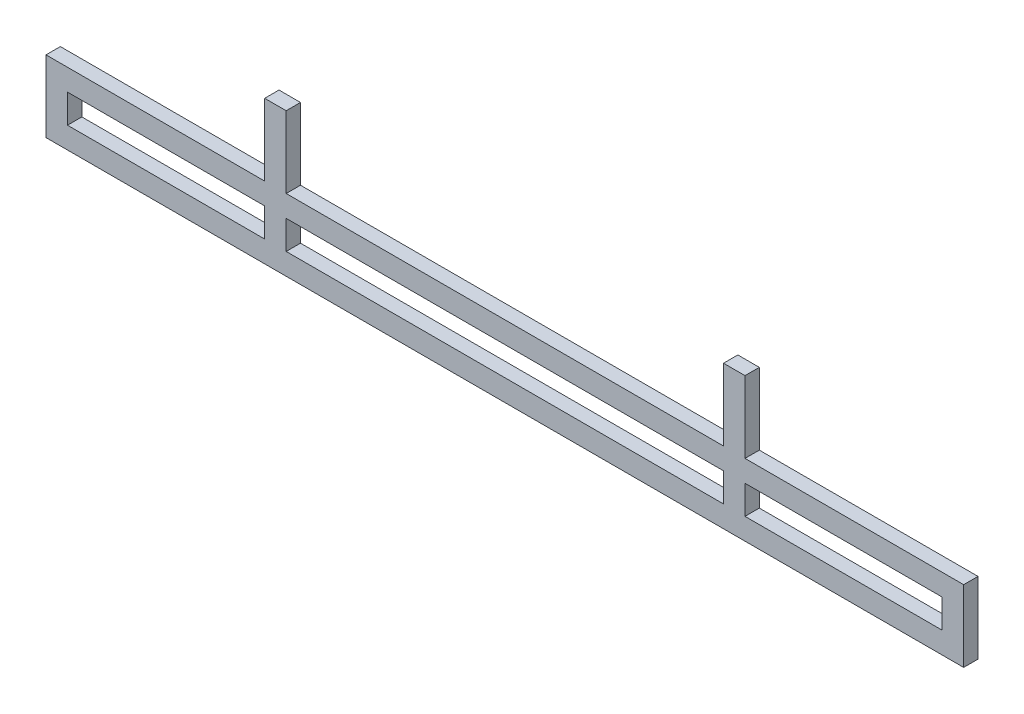
SolidWorks part; units mm, degrees
ref_plane "Front Plane" through (0, 0, 0) normal (0, 0, 1) x (1, 0, 0)
ref_plane "Top Plane" through (0, 0, 0) normal (0, 1, 0) x (1, 0, 0)
ref_plane "Right Plane" through (0, 0, 0) normal (1, 0, 0) x (0, 0, -1)
sketch "Sketch1" plane through (0, 0, 0) normal (0, 0, 1) x (1, 0, 0)
  line L1 (0, -145.36) -> (-640, -145.36)
  line L2 (0, -145.36) -> (0, -95.36)
  line L3 (0, -95.36) -> (-640, -95.36)
  line L4 (-640, -145.36) -> (-640, -95.36)
  dimension "D2" = 50
extrude "Boss-Extrude1" add sketch "Sketch1" along normal blind 10
sketch "Sketch2" plane through (0, 0, 0) normal (0, 0, 1) x (1, 0, 0)
  line L6 (-480, -145.36) -> (-480, -95.36) construction
  line L22 (-640, -95.36) -> (-640, -145.36) construction
  line L31 (-320, -145.36) -> (-320, -120.36) construction
  line L36 (-640, -145.36) -> (0, -145.36) construction
  line L37 (-320, -120.36) -> (-640, -120.36) construction
  line L38 (0, -95.36) -> (-640, -95.36) construction
  line L39 (-487.5, -95.36) -> (-472.5, -95.36)
  line L40 (-487.5, -95.36) -> (-487.5, -45.36)
  line L41 (-487.5, -45.36) -> (-472.5, -45.36)
  line L42 (-472.5, -95.36) -> (-472.5, -45.36)
  line L43 (-630, -45.36) -> (-487.5, -45.36) construction
  line L44 (-487.5, -95.36) -> (-487.5, -45.36)
  line L45 (-472.5, -95.36) -> (-472.5, -45.36)
  line L46 (-160, -145.36) -> (-160, -95.36) construction
  line L47 (-167.5, -95.36) -> (-167.5, -45.36)
  line L48 (-152.5, -95.36) -> (-152.5, -45.36)
  line L49 (-167.5, -95.36) -> (-167.5, -45.36)
  line L50 (-152.5, -45.36) -> (-167.5, -45.36)
  line L51 (-152.5, -95.36) -> (-152.5, -45.36)
  line L52 (-152.5, -95.36) -> (-167.5, -95.36)
  point P5 (-480, -120.36)
  point P19 (-480, -120.36)
  point P20 (-480, -95.36)
  line M30 (-640, -95.36) -> (0, -95.36)
  dimension "D1" = 15
extrude "Boss-Extrude2" add sketch "Sketch2" along normal blind 10 contours L50 L48 L47 M30 | L40 L39 L42 L41
sketch "Sketch3" plane through (0, 0, 0) normal (0, 0, -1) x (-1, 0, 0)
  line L0 (0, -95.36) -> (152.5, -95.36) construction
  line L1 (625, -110.36) -> (15, -110.36)
  line L2 (625, -110.36) -> (625, -130.36)
  line L3 (625, -130.36) -> (15, -130.36)
  line L4 (15, -110.36) -> (15, -130.36)
  line L5 (640, -145.36) -> (0, -145.36) construction
  line L6 (0, -145.36) -> (0, -95.36) construction
  line L7 (640, -95.36) -> (640, -145.36) construction
  dimension "D1" = 15
  dimension "D2" = 15
  dimension "D3" = 15
  dimension "D4" = 15
extrude "Cut-Extrude1" cut sketch "Sketch3" against normal blind 10 contours L2 L1 L4 L3
sketch "Sketch5" plane through (0, -45.36, 0) normal (0, 1, 0) x (1, 0, 0)
  line L0 (-160, -10) -> (-160, 0) construction
  line L1 (-152.5, -5) -> (-156.5, -5)
  line L2 (-152.5, -5) -> (-152.5, -10)
  line L3 (-152.5, -10) -> (-156.5, -10)
  line L4 (-156.5, -5) -> (-156.5, -10)
  line L5 (-152.5, -10) -> (-167.5, -10) construction
  line L6 (-152.5, 0) -> (-167.5, 0) construction
  line L7 (-163.5, -5) -> (-163.5, -10)
  line L8 (-167.5, -10) -> (-163.5, -10)
  line L9 (-167.5, -5) -> (-167.5, -10)
  line L10 (-167.5, -5) -> (-163.5, -5)
  dimension "D1" = 3.5
  dimension "D2" = 5
extrude "Cut-Extrude2" [suppressed] cut sketch "Sketch5" against normal blind 10
hole_wizard "CSK for M3 Countersunk Flat Head Screw1" [suppressed] positions "Sketch6" profile "Sketch7" countersink size "M3" standard "ISO"
sketch "Sketch6" plane through (0, 0, 10) normal (0, 0, 1) x (1, 0, 0)
  line L0 (-167.5, -50.36) -> (-152.5, -50.36) construction
  line L1 (-167.5, -55.36) -> (-167.5, -45.36) construction
  line L2 (-152.5, -95.36) -> (-152.5, -45.36) construction
  point P8 (-160, -50.36)
sketch "Sketch7" plane through (-160, -50.36, 10) normal (1, 0, 0) x (0, -1, 0)
  line L0 (0, 0) -> (0, 16.0215)
  line L1 (0, 16.0215) -> (1.7, 15)
  line L2 (1.7, 15) -> (1.7, 1.45)
  line L3 (1.7, 1.45) -> (3.15, 0)
  line L5 (3.15, 0) -> (0, 0)
  line L6 (-1.7, 1.45) -> (-3.15, 0) construction
  line L10 (0, 16.0215) -> (-1.7, 15) construction
  line L11 (0, -6.35) -> (0, 107.95) construction
  dimension "Hole Dia." = 3.4
  dimension "Hole Depth" = 15
  dimension "Near C'Sink Dia." = 6.3
  dimension "Near C'Sink Angle" = 90
  dimension "Drill Angle" = 118
sketch "Esboço1" plane through (0, 0, 10) normal (0, 0, 1) x (1, 0, 0)
  line L0 (-625, -110.36) -> (-15, -110.36) construction
  line L1 (-472.5, -110.36) -> (-487.5, -110.36)
  line L2 (-472.5, -110.36) -> (-472.5, -130.36)
  line L3 (-472.5, -130.36) -> (-487.5, -130.36)
  line L4 (-487.5, -110.36) -> (-487.5, -130.36)
  line L5 (-625, -130.36) -> (-15, -130.36) construction
  line L7 (-152.5, -110.36) -> (-167.5, -110.36)
  line L8 (-152.5, -110.36) -> (-152.5, -130.36)
  line L9 (-152.5, -130.36) -> (-167.5, -130.36)
  line L10 (-167.5, -110.36) -> (-167.5, -130.36)
extrude "Ressalto-extrusão1" add sketch "Esboço1" against normal blind 10
